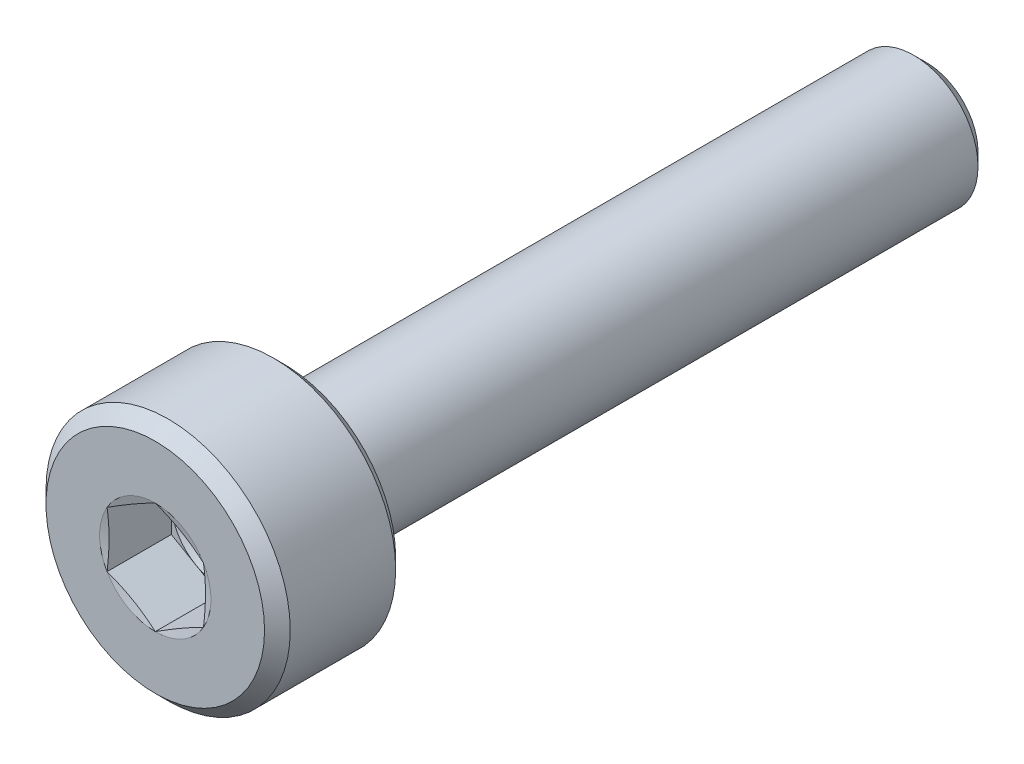
SolidWorks part; units mm, degrees
ref_plane "Front Plane" through (0, 0, 0) normal (0, 0, 1) x (1, 0, 0)
ref_plane "Top Plane" through (0, 0, 0) normal (0, 1, 0) x (1, 0, 0)
ref_plane "Right Plane" through (0, 0, 0) normal (1, 0, 0) x (0, 0, -1)
sketch "Sketch1" plane through (0, 0, 0) normal (1, 0, 0) x (0, 0, -1)
  line L0 (0, 0) -> (12.9407, 0) construction
  line L1 (0, 0) -> (0, 1.7)
  line L2 (0, 1.7) -> (0.2, 1.9)
  line L3 (0.2, 1.9) -> (1.84, 1.9)
  line L4 (2, 1.74) -> (2, 1.3)
  line L5 (2.51, 1) -> (11.8, 1)
  line L6 (11.8, 1) -> (12, 0.8)
  line L7 (12, 0.8) -> (12, 0)
  line L8 (12, 0) -> (0, 0)
  line L9 (1.84, 1.9) -> (2, 1.74)
  line L10 (2.4662, 1.0101) -> (2.0562, 1.2101)
  arc A2 (2.51, 1) -> (2.4662, 1.0101) centre (2.51, 1.1) cw
  arc A3 (2.0562, 1.2101) -> (2, 1.3) centre (2.1, 1.3) cw
  point P6 (2, 1.9)
  dimension "R2" = 0.1
  dimension "R1" = 0.1
  dimension "D1" = 45
  dimension "DK" = 3.8
  dimension "D3" = 45
  dimension "length" = 10
  dimension "K" = 2
  dimension "V" = 0.2
  dimension "HOLESIZE" = 2
  dimension "D4" = 1.6
  dimension "D5" = 45
  dimension "DW" = 3.48
  dimension "F" = 0.51
  dimension "DA" = 2.6
revolve "Revolve1" add sketch "Sketch1" angle 360 about L0
cosmetic thread "Cosmetic Thread1" parameters "D1"=8.8, "D2"=2
sketch "Sketch2" plane through (0, 0, 0) normal (0, 0, 1) x (1, 0, 0)
  line L0 (0, 0) -> (0, 0.866) construction
  line L2 (0, 0.866) -> (-0.75, 0.433)
  line L3 (-0.75, 0.433) -> (-0.75, -0.433)
  line L4 (-0.75, -0.433) -> (0, -0.866)
  line L5 (0, -0.866) -> (0.75, -0.433)
  line L6 (0.75, -0.433) -> (0.75, 0.433)
  line L7 (0.75, 0.433) -> (0, 0.866)
  circle A0 centre (0, 0) radius 0.75 construction
  dimension "S" = 1.5
extrude "Cut-Extrude1" cut sketch "Sketch2" against normal blind 1
sketch "Sketch3" plane through (0, 0, 0) normal (1, 0, 0) x (0, 0, -1)
  line L0 (1, 0) -> (12, 0) construction
  line L1 (12, -0.8) -> (12, 0.8) construction
  line L2 (1, 0) -> (1, 0.75)
  line L4 (1, 0.75) -> (1.433, 0)
  line L5 (1.433, 0) -> (1, 0)
  line L6 (0, 1.7) -> (0, -1.7) construction
  dimension "DRILLANG" = 60
  dimension "DRILL DEPTH" = 1
  dimension "S2" = 1.5
revolve "Cut-Revolve2" cut sketch "Sketch3" angle 360 about L0
sketch "Sketch4" plane through (0, 0, 0) normal (1, 0, 0) x (0, 0, -1)
  line L0 (0, 0) -> (4.6121, 0) construction
  line L1 (0, 0.866) -> (0, 0.75)
  line L2 (0, 1.7) -> (0, -1.7) construction
  line L3 (0, 0.75) -> (0.0311, 0.75)
  line L4 (0.0311, 0.75) -> (0, 0.866)
  point P12 (0.0155, 0.75)
  dimension "D1" = 1.5
  dimension "D2" = 15
revolve "Cut-Revolve3" cut sketch "Sketch4" angle 360 about L0
